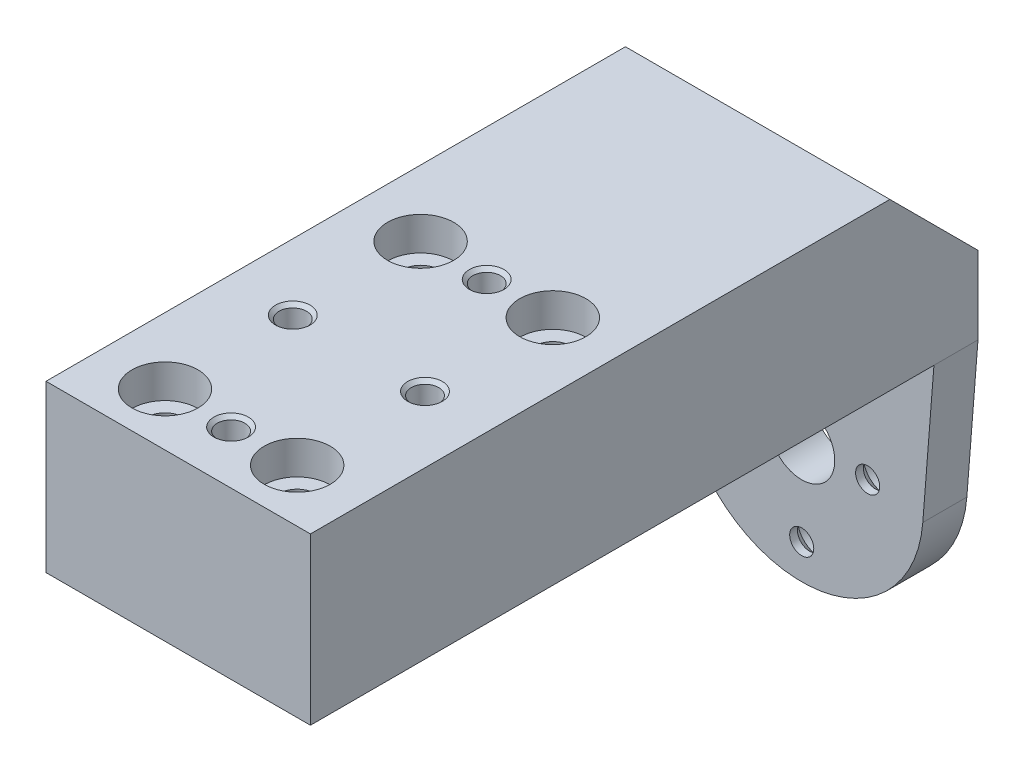
SolidWorks part; units mm, degrees
material "ABS"
ref_plane "Front Plane" through (0, 0, 0) normal (0, 0, 1) x (1, 0, 0)
ref_plane "Top Plane" through (0, 0, 0) normal (0, 1, 0) x (1, 0, 0)
ref_plane "Right Plane" through (0, 0, 0) normal (1, 0, 0) x (0, 0, -1)
sketch "Sketch1" plane through (0, 0, 0) normal (0, 0, 1) x (1, 0, 0)
  line L1 (-19.05, -11.938) -> (19.05, -11.938)
  line L2 (-19.05, -11.938) -> (-19.05, 11.938)
  line L3 (-19.05, 11.938) -> (19.05, 11.938)
  line L4 (19.05, -11.938) -> (19.05, 11.938)
  line L5 (-19.05, -11.938) -> (19.05, 11.938) construction
  line L6 (-19.05, 11.938) -> (19.05, -11.938) construction
  point P0 (0, 0)
  dimension "D1" = 23.876
  dimension "D2" = 38.1
extrude "Gearbox Mount" add sketch "Sketch1" along normal blind 48.26
sketch "Gearbox Hole Pattern" plane through (0, 11.938, 0) normal (0, 1, 0) x (1, 0, 0)
  line L1 (9.525, -40.64) -> (-9.525, -40.64) construction
  line L2 (9.525, -40.64) -> (9.525, -3.81) construction
  line L3 (9.525, -3.81) -> (-9.525, -3.81) construction
  line L4 (-9.525, -40.64) -> (-9.525, -3.81) construction
  line L5 (9.525, -40.64) -> (-9.525, -3.81) construction
  line L6 (9.525, -3.81) -> (-9.525, -40.64) construction
  line L7 (19.05, -48.26) -> (19.05, 0) construction
  line L8 (19.05, -48.26) -> (-19.05, -48.26) construction
  point P0 (0, -22.225)
  dimension "D1" = 19.05
  dimension "D2" = 36.83
  dimension "D3" = 44.45
  dimension "D4" = 19.05
hole_wizard "CBORE for #4 Socket Head Cap Screw1" positions "Sketch6" profile "Sketch5" counterbore size "#4" standard "ANSI Inch"
sketch "Sketch6" plane through (0, 11.938, 0) normal (0, 1, 0) x (1, 0, 0)
  line L0 (9.525, -3.81) -> (-9.525, -3.81) construction
  line L1 (-9.525, -40.64) -> (-9.525, -3.81) construction
  line L2 (9.525, -40.64) -> (-9.525, -40.64) construction
  line L3 (9.525, -40.64) -> (9.525, -3.81) construction
  point P0 (0, -3.81)
  point P4 (-9.525, -22.225)
  point P8 (0, -40.64)
  point P12 (9.525, -22.225)
sketch "Sketch5" plane through (0, 11.938, 3.81) normal (1, 0, 0) x (0, 0, 1)
  line L0 (0, 0) -> (0, 13.6806)
  line L1 (0, 13.6806) -> (1.6319, 12.7)
  line L2 (1.6319, 12.7) -> (1.6319, 4.7625)
  line L3 (1.6319, 4.7625) -> (1.9844, 4.7625)
  line L4 (1.9844, 4.7625) -> (1.9844, 0)
  line L5 (1.9844, 0) -> (0, 0)
  line L10 (0, 13.6806) -> (-1.632, 12.7) construction
  line L11 (0, -6.35) -> (0, 107.95) construction
  dimension "Hole Dia." = 3.2639
  dimension "Hole Depth" = 12.7
  dimension "C'Bore Dia." = 3.9688
  dimension "C'Bore Depth" = 4.7625
  dimension "Drill Angle" = 118
chamfer "Insert Installation Chamfers" distance 0.508 angle 45 4 edges at (0, 11.938, 42.6244) (9.525, 11.938, 24.2094) (0, 11.938, 5.7944) (-9.525, 11.938, 24.2094)
sketch "Sketch7" plane through (0, 0, 0) normal (0, 0, -1) x (-1, 0, 0)
  line L1 (-19.05, -11.938) -> (19.05, -11.938)
  line L2 (-19.05, -11.938) -> (-19.05, 11.938)
  line L3 (-19.05, 11.938) -> (19.05, 11.938)
  line L4 (19.05, -11.938) -> (19.05, 11.938)
  line L5 (-19.05, -11.938) -> (19.05, 11.938) construction
  line L6 (-19.05, 11.938) -> (19.05, -11.938) construction
  point P0 (0, 0)
extrude "Motor Mount Extension" add sketch "Sketch7" along normal blind 41.5798
hole_wizard "CBORE for #10 Socket Head Cap Screw1" positions "Sketch4" profile "Sketch3" counterbore size "#10" standard "ANSI Inch" end condition through all
sketch "Sketch4" plane through (0, 11.938, 0) normal (0, 1, 0) x (1, 0, 0)
  point P0 (-9.525, -40.64)
  point P3 (9.525, -40.64)
  point P7 (9.525, -3.81)
  point P10 (-9.525, -3.81)
sketch "Sketch3" plane through (-9.525, 11.938, 40.64) normal (1, 0, 0) x (0, 0, 1)
  line L0 (0, 0) -> (0, 23.876)
  line L1 (0, 23.876) -> (2.5527, 23.876)
  line L3 (2.5527, 23.876) -> (2.5527, 4.826)
  line L4 (2.5527, 4.826) -> (4.7625, 4.826)
  line L5 (4.7625, 4.826) -> (4.7625, 0)
  line L7 (4.7625, 0) -> (0, 0)
  line L11 (0, -6.35) -> (0, 107.95) construction
  dimension "Thru Hole Dia." = 5.1054
  dimension "Thru Hole Depth" = 23.876
  dimension "C'Bore Dia." = 9.525
  dimension "C'Bore Depth" = 4.826
sketch "Sketch8" plane through (0, 0, -41.5798) normal (0, 0, -1) x (-1, 0, 0)
  line L0 (19.05, 11.938) -> (-19.05, 11.938)
  line L1 (-19.05, 11.938) -> (-19.05, -11.938) construction
  line L2 (19.05, 11.938) -> (-19.05, 11.938) construction
  line L3 (-19.05, 11.938) -> (-19.05, -11.938)
  line L4 (19.05, 11.938) -> (19.05, -11.938)
  line L5 (-19.05, -11.938) -> (19.05, -11.938) construction
  line L6 (-19.05, -11.938) -> (-17.4463, -32.3582)
  line L7 (19.05, -11.938) -> (17.4463, -32.3582)
  line L8 (0, 0) -> (0, -30.988) construction
  arc A0 (-17.4463, -32.3582) -> (17.4463, -32.3582) centre (0, -30.988) ccw
  dimension "D2" = 17.5
  dimension "D1" = 19.05
extrude "Motor Mount Plate" add sketch "Sketch8" along normal blind 6.35
sketch "Sketch9" plane through (0, 0, -47.9298) normal (0, 0, -1) x (-1, 0, 0)
  circle A0 centre (0, -30.988) radius 4.7625
  arc A1 (-17.4463, -32.3582) -> (17.4463, -32.3582) centre (0, -30.988) ccw construction
  dimension "D1" = 9.525
extrude "Shaft Clearance" cut sketch "Sketch9" against normal up to next
hole_wizard "CSK for M3 Flat Head Machine Screw1" positions "Sketch11" profile "Sketch10" countersink size "M3" standard "ANSI Metric" end condition up to next
sketch "Sketch11" plane through (0, 0, -47.9298) normal (0, 0, -1) x (-1, 0, 0)
  circle A0 centre (0, -30.988) radius 9.5 construction
  circle A1 centre (0, -30.988) radius 12.5 construction
  circle A3 centre (0, -30.988) radius 4.7625 construction
  point P9 (-9.5, -30.988)
  point P11 (9.5, -30.988)
  point P13 (0, -18.488)
  point P15 (0, -43.488)
  dimension "D1" = 25
  dimension "D2" = 19
sketch "Sketch10" plane through (9.5, -30.988, -47.9298) normal (1, 0, 0) x (0, 1, 0)
  line L0 (0, 0) -> (0, 6.35)
  line L1 (0, 6.35) -> (1.7, 6.35)
  line L2 (1.7, 6.35) -> (1.7, 5.26)
  line L3 (1.7, 5.26) -> (3.15, 3.81)
  line L4 (3.15, 3.81) -> (3.15, 0)
  line L6 (3.15, 0) -> (0, 0)
  line L7 (-1.7, 5.26) -> (-3.15, 3.81) construction
  line L11 (0, -6.35) -> (0, 107.95) construction
  dimension "Thru Hole Dia." = 3.4
  dimension "Thru Hole Depth" = 6.35
  dimension "C'Sink Dia." = 6.3
  dimension "C'Sink Angle" = 90
  dimension "Head Clearance" = 3.81
chamfer "Chamfer2" distance 12.7 angle 45 1 edges at (0, 11.938, -47.9298)
sketch "Sketch12" plane through (0, 7.112, 0) normal (0, 1, 0) x (1, 0, 0)
  circle A35 centre (-9.525, -3.81) radius 2.6035
  circle A36 centre (9.525, -3.81) radius 2.6035
  circle A37 centre (-9.525, -40.64) radius 2.6035
  circle A38 centre (9.525, -40.64) radius 2.6035
  dimension "D1" = 5.207
extrude "Cut-Extrude1" cut sketch "Sketch12" against normal up to next
sketch "Sketch13" plane through (0, 0, -41.5798) normal (0, 0, 1) x (1, 0, 0)
  circle A0 centre (0, -18.488) radius 1.7348
  circle A1 centre (-9.5, -30.988) radius 1.7348
  circle A2 centre (9.5, -30.988) radius 1.7348
  circle A3 centre (0, -43.488) radius 1.7348
  dimension "D1" = 3.4696
extrude "Cut-Extrude2" cut sketch "Sketch13" against normal through all
